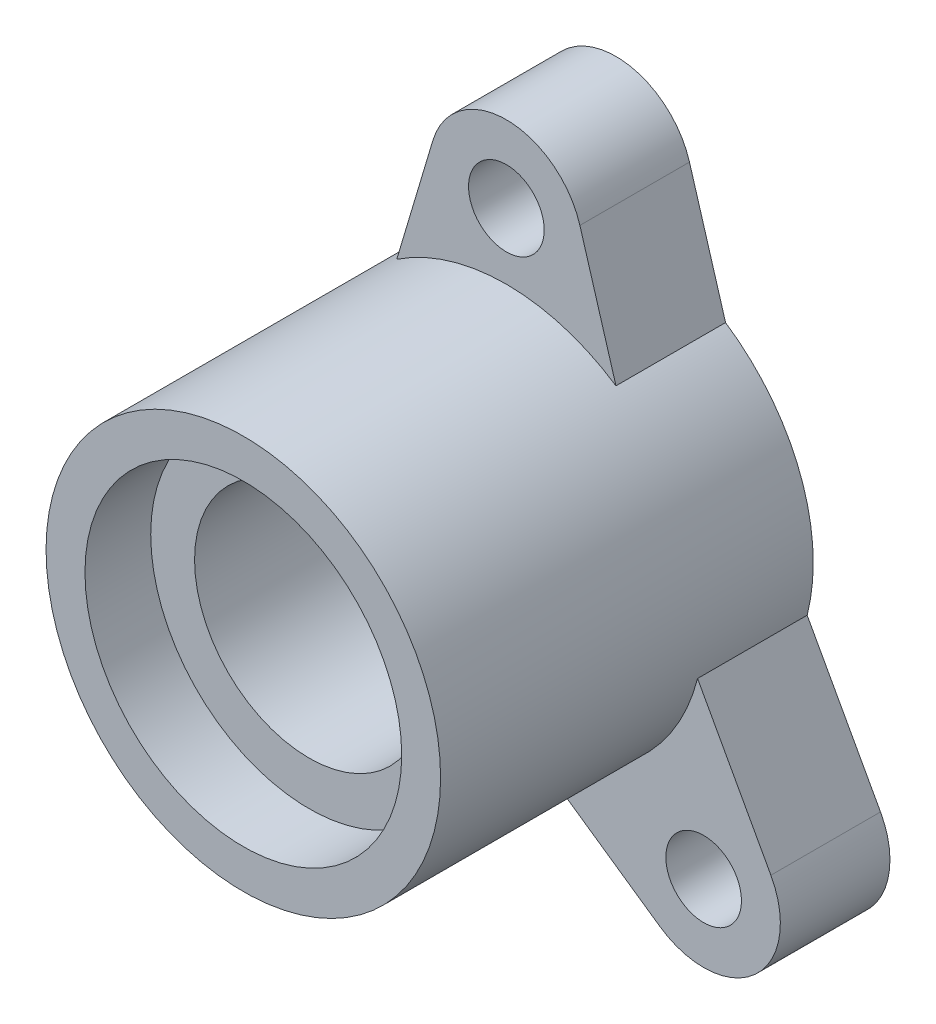
SolidWorks part; units mm, degrees
material "ABS"
ref_plane "Front Plane" through (0, 0, 0) normal (0, 0, 1) x (1, 0, 0)
ref_plane "Top Plane" through (0, 0, 0) normal (0, 1, 0) x (1, 0, 0)
ref_plane "Right Plane" through (0, 0, 0) normal (1, 0, 0) x (0, 0, -1)
sketch "Sketch1" plane through (0, 0, 0) normal (0, 0, 1) x (1, 0, 0)
  line L0 (-9, 0) -> (9, 0) construction
  line L1 (0, 0) -> (9, -10) construction
  line L2 (0, 12) -> (0, -9) construction
  line L3 (8.7225, -2.2175) -> (12.0686, -8.3166)
  line L4 (1.2896, -8.9071) -> (7.0037, -12.8749)
  line L6 (-8.7225, -2.2175) -> (-12.0686, -8.3166)
  line L7 (-1.2896, -8.9071) -> (-7.0037, -12.8749)
  line L8 (0, 0) -> (-9, -10) construction
  line L12 (-3.3539, 13.0006) -> (-5, 7.4833)
  line L13 (3.3539, 13.0006) -> (5, 7.4833)
  arc A0 (-5, 7.4833) -> (-8.7225, -2.2175) centre (0, 0) ccw
  circle A1 centre (0, 0) radius 5.225
  arc A2 (7.0037, -12.8749) -> (12.0686, -8.3166) centre (9, -10) ccw
  circle A3 centre (9, -10) radius 1.725
  circle A4 centre (-9, -10) radius 1.725
  arc A5 (-7.0037, -12.8749) -> (-12.0686, -8.3166) centre (-9, -10) cw
  circle A6 centre (0, 0) radius 9 construction
  arc A7 (-1.2896, -8.9071) -> (1.2896, -8.9071) centre (0, 0) ccw
  arc A8 (8.7225, -2.2175) -> (5, 7.4833) centre (0, 0) ccw
  circle A10 centre (0, 12) radius 1.725
  arc A11 (3.3539, 13.0006) -> (-3.3539, 13.0006) centre (0, 12) ccw
  dimension "D2" = 10.45
  dimension "D4" = 3.45
  dimension "D5" = 3.5
  dimension "D9" = 12
  dimension "D8" = 18
  dimension "D3" = 18
  dimension "D6" = 10
  dimension "D7" = 10
  dimension "D10" = 10
extrude "Boss-Extrude1" add sketch "Sketch1" along normal blind 5
sketch "Sketch2" plane through (0, 0, 5) normal (0, 0, 1) x (1, 0, 0)
  circle A0 centre (0, 0) radius 5.225
  circle A1 centre (0, 0) radius 9
  arc A2 (-5, 7.4833) -> (-8.7225, -2.2175) centre (0, 0) ccw construction
  circle A3 centre (0, 0) radius 5.225 construction
extrude "Boss-Extrude2" add sketch "Sketch2" along normal blind 12
sketch "Sketch3" plane through (0, 0, 17) normal (0, 0, 1) x (1, 0, 0)
  circle A0 centre (0, 0) radius 7.225
  circle A1 centre (0, 0) radius 5.225 construction
  circle A2 centre (0, 0) radius 5.225
  dimension "D1" = 14.45
extrude "Cut-Extrude1" cut sketch "Sketch3" against normal blind 3
equation "\"D4@Sketch1\"=3+\"print_free@Parameters@FabricationParameters.sldprt\""
equation "\"D2@Sketch1\"=10+\"print_free@Parameters@FabricationParameters.sldprt\""
equation "\"D1@Sketch3\"=14+\"print_free@Parameters@FabricationParameters.sldprt\""
